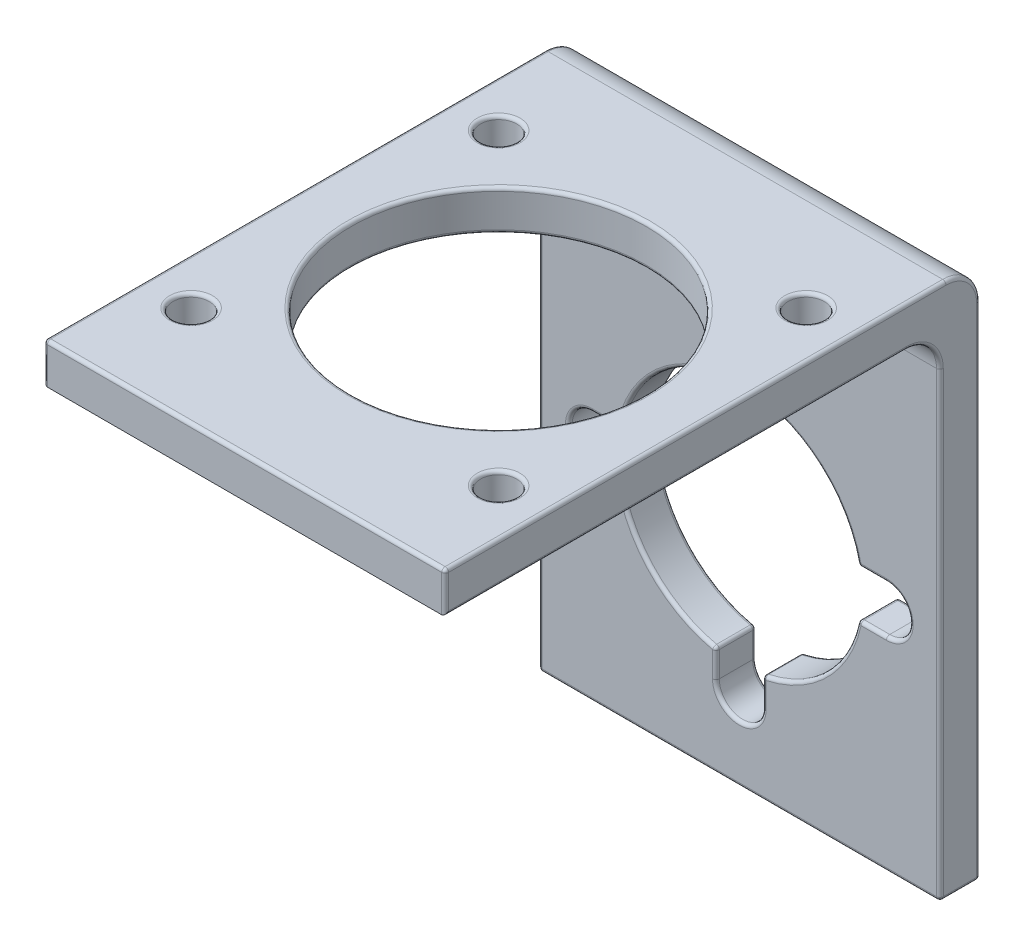
SolidWorks part; units mm, degrees
ref_plane "Front Plane" through (0, 0, 0) normal (0, 0, 1) x (1, 0, 0)
ref_plane "Top Plane" through (0, 0, 0) normal (0, 1, 0) x (1, 0, 0)
ref_plane "Right Plane" through (0, 0, 0) normal (1, 0, 0) x (0, 0, -1)
sketch "Sketch1" plane through (0, 0, 0) normal (0, 0, 1) x (1, 0, 0)
  line L1 (0, 0) -> (30, 0)
  line L2 (0, 0) -> (0, 40)
  line L3 (0, 40) -> (30, 40)
  line L4 (30, 0) -> (30, 40)
  dimension "D1" = 30
  dimension "D2" = 40
extrude "Boss-Extrude1" add sketch "Sketch1" along normal blind 3
sketch "Sketch2" plane through (0, 0, 3) normal (0, 0, 1) x (1, 0, 0)
  line L0 (30, 0) -> (30, 40) construction
  line L1 (0, 40) -> (30, 40)
  line L2 (0, 40) -> (0, 37)
  line L3 (0, 37) -> (30, 37)
  line L4 (30, 40) -> (30, 37)
  dimension "D1" = 3
extrude "Boss-Extrude2" add sketch "Sketch2" along normal blind 37
sketch "Sketch3" plane through (0, 37, 0) normal (0, -1, 0) x (-1, 0, 0)
  line L0 (0, -21) -> (-30, -21) construction
  line L1 (0, -40) -> (0, -3) construction
  line L2 (-30, -40) -> (-30, -3) construction
  line L3 (0, -40) -> (-30, -40) construction
  circle A0 centre (-15, -21) radius 11.05
  dimension "D2" = 22.1
  dimension "D1" = 19
extrude "Cut-Extrude1" cut sketch "Sketch3" against normal through all
hole_wizard "M2.5 Clearance Hole1" positions "Sketch4" profile "Sketch5" hole size "M2.5" standard "ANSI Metric" end condition through all
sketch "Sketch4" plane through (0, 40, 0) normal (0, 1, 0) x (1, 0, 0)
  line L1 (3.5, -9.5) -> (26.5, -9.5) construction
  line L2 (3.5, -9.5) -> (3.5, -32.5) construction
  line L3 (3.5, -32.5) -> (26.5, -32.5) construction
  line L4 (26.5, -9.5) -> (26.5, -32.5) construction
  line L5 (3.5, -9.5) -> (26.5, -32.5) construction
  line L6 (3.5, -32.5) -> (26.5, -9.5) construction
  point P1 (26.5, -32.5)
  point P248 (3.5, -9.5)
  point P249 (3.5, -32.5)
  point P250 (26.5, -9.5)
  dimension "D1" = 23
  dimension "D2" = 23
sketch "Sketch5" plane through (26.5, 40, 32.5) normal (1, 0, 0) x (0, 0, 1)
  line L0 (0, 0) -> (0, 40)
  line L1 (0, 40) -> (1.35, 40)
  line L2 (1.35, 40) -> (1.35, 0)
  line L5 (1.35, 0) -> (0, 0)
  line L11 (0, -6.35) -> (0, 107.95) construction
  dimension "Thru Hole Dia." = 2.7
  dimension "Thru Hole Depth" = 40
sketch "Sketch6" plane through (0, 0, 3) normal (0, 0, 1) x (1, 0, 0)
  line L0 (15, 37) -> (15, 27.98) construction
  line L1 (0, 37) -> (30, 37) construction
  line L2 (0, 0) -> (30, 0) construction
  line L3 (0, 37) -> (0, 0) construction
  line L4 (0, 37) -> (30, 37) construction
  line L5 (26, 18.73) -> (23.8996, 18.73)
  line L6 (26, 15.23) -> (23.8996, 15.23)
  line L7 (16.75, 27.98) -> (16.75, 25.8796)
  line L8 (13.25, 5.98) -> (13.25, 8.0804)
  line L12 (16.75, 8.0804) -> (16.75, 5.98)
  line L14 (15, 4.23) -> (15, 0) construction
  line L16 (6.1004, 18.73) -> (4, 18.73)
  line L17 (6.1004, 15.23) -> (4, 15.23)
  line L19 (13.25, 25.8796) -> (13.25, 27.98)
  arc A0 (23.8996, 18.73) -> (16.75, 25.8796) centre (15, 16.98) ccw
  arc A1 (16.75, 8.0804) -> (23.8996, 15.23) centre (15, 16.98) ccw
  arc A2 (16.75, 27.98) -> (13.25, 27.98) centre (15, 27.98) ccw
  arc A3 (13.25, 5.98) -> (16.75, 5.98) centre (15, 5.98) ccw
  arc A4 (26, 15.23) -> (26, 18.73) centre (26, 16.98) ccw
  arc A5 (4, 18.73) -> (4, 15.23) centre (4, 16.98) ccw
  arc A7 (13.25, 25.8796) -> (6.1004, 18.73) centre (15, 16.98) ccw
  arc A8 (6.1004, 15.23) -> (13.25, 8.0804) centre (15, 16.98) ccw
  point P12 (15, 16.98)
  point P15 (15, 16.015)
  dimension "D1" = 16.98
  dimension "D2" = 18.14
  dimension "D3" = 4
  dimension "D4" = 3.5
  dimension "D5" = 20.985
extrude "Cut-Extrude2" cut sketch "Sketch6" against normal through all
fillet "Fillet1" radius 2.54 2 edges at (15, 37, 3) (15, 40, 0)
fillet "Fillet2" radius 0.254 69 edges at (0, 36.2561, 3.7439) (30, 36.2561, 3.7439) (30, 39.2561, 0.7439) (0, 39.2561, 0.7439) (0, 0, 1.5) (30, 0, 1.5) (30, 40, 21.27) (0, 40, 21.27) (30, 17.23, 3) (15, 0, 3) (0, 17.23, 3) (30, 18.73, 0) (15, 0, 0) (0, 18.73, 0) (0, 37, 22.77) (30, 37, 22.77) (15, 40, 40) (30, 38.5, 40) (0, 38.5, 40) (15, 40, 9.95) (15, 37, 9.95) (26.5, 37, 10.85) (26.5, 40, 10.85) (3.5, 37, 33.85) (3.5, 40, 33.85) (3.5, 37, 10.85) (3.5, 40, 10.85) (26.5, 37, 33.85) (26.5, 40, 33.85) (6.1004, 15.23, 1.5) (6.1004, 18.73, 1.5) (13.25, 25.8796, 1.5) (16.75, 25.8796, 1.5) (23.8996, 18.73, 1.5) (23.8996, 15.23, 1.5) (16.75, 8.0804, 1.5) (13.25, 8.0804, 1.5) (5.0502, 15.23, 0) (2.25, 16.98, 0) (5.0502, 18.73, 0) (8.5865, 23.3935, 0) (13.25, 26.9298, 0) (15, 29.73, 0) (16.75, 26.9298, 0) (21.4135, 23.3935, 0) (24.9498, 18.73, 0) (27.75, 16.98, 0) (24.9498, 15.23, 0) (21.4135, 10.5665, 0) (16.75, 7.0302, 0) (15, 4.23, 0) (13.25, 7.0302, 0) (8.5865, 10.5665, 0) (5.0502, 15.23, 3) (2.25, 16.98, 3) (5.0502, 18.73, 3) (8.5865, 23.3935, 3) (13.25, 26.9298, 3) (15, 29.73, 3) (16.75, 26.9298, 3) (21.4135, 23.3935, 3) (24.9498, 18.73, 3) (27.75, 16.98, 3) (24.9498, 15.23, 3) (21.4135, 10.5665, 3) (16.75, 7.0302, 3) (15, 4.23, 3) (13.25, 7.0302, 3) (8.5865, 10.5665, 3)
